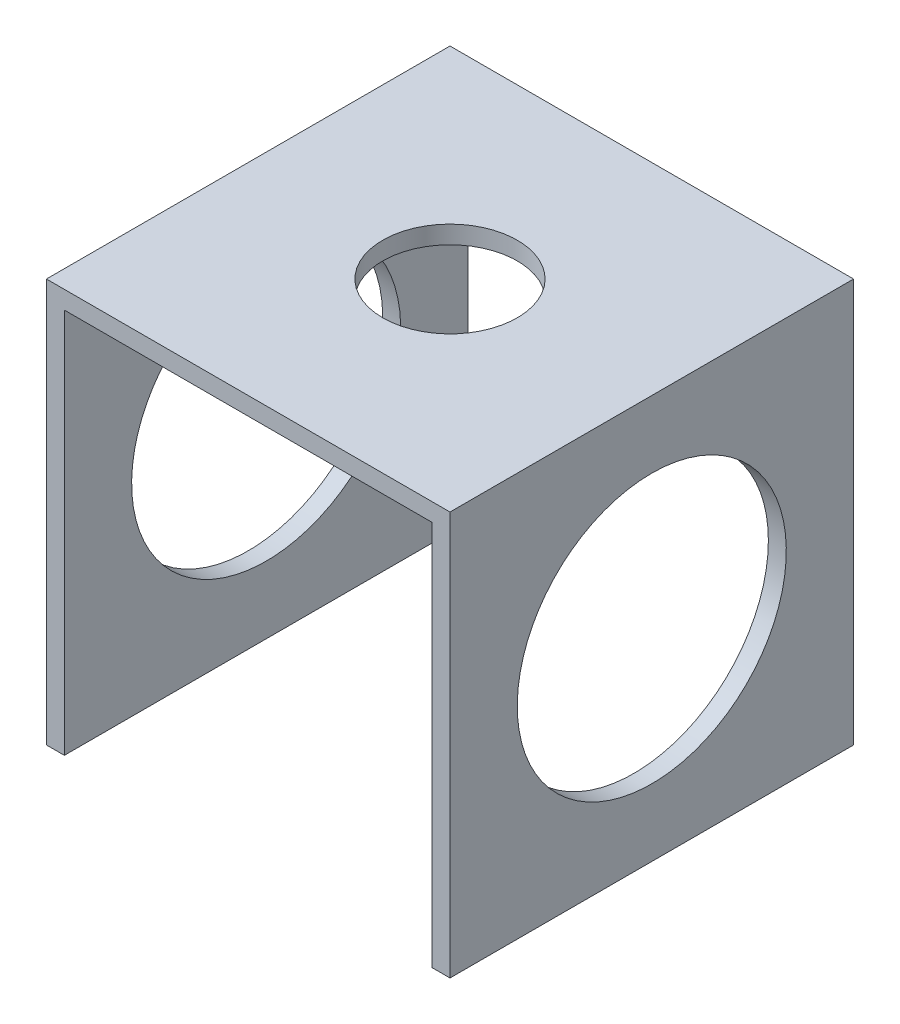
SolidWorks part; units mm, degrees
ref_plane "前视基准面" through (0, 0, 0) normal (0, 0, 1) x (1, 0, 0)
ref_plane "上视基准面" through (0, 0, 0) normal (0, 1, 0) x (1, 0, 0)
ref_plane "右视基准面" through (0, 0, 0) normal (1, 0, 0) x (0, 0, -1)
other "Configuration Table"
sketch "草图1" plane through (0, 0, 0) normal (0, 0, 1) x (1, 0, 0)
  line L0 (0, 0) -> (0, 218.3382) construction
  line L1 (-90, 180) -> (90, 180)
  line L2 (90, 180) -> (90, 0)
  line L3 (90, 0) -> (82, 0)
  line L4 (82, 0) -> (82, 172)
  line L5 (82, 172) -> (-82, 172)
  line L6 (-82, 0) -> (-82, 172)
  line L7 (-90, 0) -> (-82, 0)
  line L8 (-90, 180) -> (-90, 0)
  point P5 (0, 218.3382)
  point P11 (0, 172)
  point P14 (0, 180)
  dimension "D1" = 8
  dimension "D2" = 8
  dimension "D3" = 180
  dimension "D4" = 90
extrude "凸台-拉伸1" add sketch "草图1" along normal blind 180
sketch "草图2" plane through (0, 180, 0) normal (0, 1, 0) x (1, 0, 0)
  line L0 (-107.1953, -90) -> (124.7074, -90) construction
  line L1 (0, 14.5236) -> (0, -191.0225) construction
  line L2 (90, 0) -> (-90, 0) construction
  line L3 (90, -180) -> (-90, -180) construction
  circle A0 centre (0, -90) radius 30
  point P11 (0, 0)
  dimension "D1" = 60
extrude "切除-拉伸1" cut sketch "草图2" against normal blind 180
sketch "草图3" plane through (90, 0, 0) normal (1, 0, 0) x (0, 0, -1)
  line L0 (-202.0275, 90) -> (22.0275, 90) construction
  line L1 (-90, 182.9754) -> (-90, -6.0566) construction
  line L2 (-180, 0) -> (0, 0) construction
  line L3 (-180, 180) -> (0, 180) construction
  line L4 (0, 0) -> (0, 180) construction
  line L5 (-180, 0) -> (-180, 180) construction
  circle A0 centre (-90, 90) radius 60
  point P14 (-66.9167, 90)
  point P15 (0, 0)
  dimension "D1" = 120
extrude "切除-拉伸2" cut sketch "草图3" against normal blind 217 contours A0
